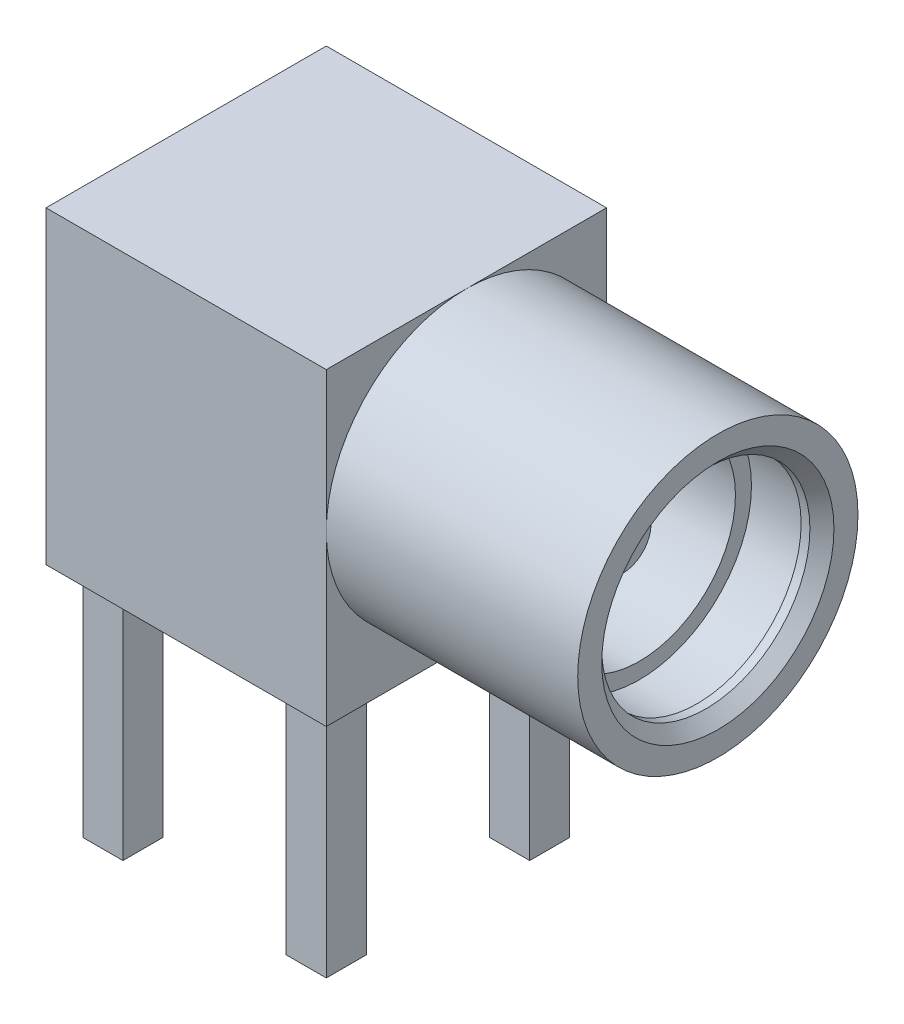
SolidWorks part; units mm, degrees
ref_plane "Front Plane" through (0, 0, 0) normal (0, 0, 1) x (1, 0, 0)
ref_plane "Top Plane" through (0, 0, 0) normal (0, 1, 0) x (1, 0, 0)
ref_plane "Right Plane" through (0, 0, 0) normal (1, 0, 0) x (0, 0, -1)
ref_plane "Plane1" through (0, 0, 20.79) normal (0, 0, -1) x (-1, 0, 0)
sketch "Sketch1" plane through (0, 0, 20.79) normal (0, 0, -1) x (-1, 0, 0)
  line L0 (-38.0125, -41.9) -> (-41.5125, -41.9)
  line L1 (-41.5125, -41.9) -> (-41.5125, -45.76)
  line L2 (-41.5125, -45.76) -> (-38.0125, -45.76)
  line L3 (-38.0125, -45.76) -> (-38.0125, -41.9)
extrude "Boss-Extrude1" add sketch "Sketch1" against normal blind 3.5
sketch "Sketch2" plane through (41.5125, 0, 0) normal (1, 0, 0) x (0, 0, -1)
  circle A0 centre (-22.54, -43.65) radius 1.75
extrude "Boss-Extrude2" add sketch "Sketch2" along normal blind 3.14
sketch "Sketch3" plane through (0, -45.76, 0) normal (0, -1, 0) x (1, 0, 0)
  line L0 (38.7425, 24.06) -> (38.7425, 23.56)
  line L1 (38.7425, 23.56) -> (38.2425, 23.56)
  line L2 (38.2425, 23.56) -> (38.2425, 24.06)
  line L3 (38.2425, 24.06) -> (38.7425, 24.06)
extrude "Boss-Extrude3" add sketch "Sketch3" along normal blind 2.95
sketch "Sketch4" plane through (0, -45.76, 0) normal (0, -1, 0) x (1, 0, 0)
  line L0 (41.2825, 21.52) -> (41.2825, 21.02)
  line L1 (41.2825, 21.02) -> (40.7825, 21.02)
  line L2 (40.7825, 21.02) -> (40.7825, 21.52)
  line L3 (40.7825, 21.52) -> (41.2825, 21.52)
extrude "Boss-Extrude4" add sketch "Sketch4" along normal blind 2.95
sketch "Sketch5" plane through (0, -45.76, 0) normal (0, -1, 0) x (1, 0, 0)
  line L0 (38.7425, 21.52) -> (38.7425, 21.02)
  line L1 (38.7425, 21.02) -> (38.2425, 21.02)
  line L2 (38.2425, 21.02) -> (38.2425, 21.52)
  line L3 (38.2425, 21.52) -> (38.7425, 21.52)
extrude "Boss-Extrude5" add sketch "Sketch5" along normal blind 2.95
sketch "Sketch6" plane through (0, -45.76, 0) normal (0, -1, 0) x (1, 0, 0)
  line L0 (41.2825, 24.06) -> (41.2825, 23.56)
  line L1 (41.2825, 23.56) -> (40.7825, 23.56)
  line L2 (40.7825, 23.56) -> (40.7825, 24.06)
  line L3 (40.7825, 24.06) -> (41.2825, 24.06)
extrude "Boss-Extrude6" add sketch "Sketch6" along normal blind 2.95
hole_wizard "#2 Clearance Hole1" positions "Sketch8" profile "Sketch7" hole size "#2" standard "ANSI Inch"
sketch "Sketch8" plane through (44.6525, 0, 0) normal (1, 0, 0) x (0, 0, -1)
  point P0 (-22.54, -43.65)
sketch "Sketch7" plane through (44.6525, -43.65, 22.54) normal (0, 1, 0) x (0, 0, -1)
  line L0 (0, 0) -> (0, 2.59)
  line L1 (0, 2.59) -> (1.2, 2.59)
  line L2 (1.2, 2.59) -> (1.2, 0)
  line L5 (1.2, 0) -> (0, 0)
  line L10 (0, 2.59) -> (-1.2, 2.59) construction
  line L11 (0, -6.35) -> (0, 107.95) construction
  dimension "Hole Dia." = 2.4
  dimension "Hole Depth" = 2.59
  dimension "Drill Angle" = 180
ref_plane "Plane2" through (0, 0, 22.54) normal (0, 0, 1) x (1, 0, 0)
sketch "Sketch9" plane through (0, 0, 22.54) normal (0, 0, 1) x (1, 0, 0)
  line L0 (40.1175, -45.76) -> (39.7625, -45.76)
  line L1 (39.7625, -45.76) -> (39.7625, -48.71)
  line L2 (39.7625, -48.71) -> (39.9675, -48.71)
  line L3 (39.9675, -48.71) -> (40.1175, -48.56)
  line L4 (40.1175, -48.56) -> (40.1175, -45.76)
  line L5 (39.7625, -45.76) -> (39.7625, -48.71) construction
revolve "Revolve1" add sketch "Sketch9" angle 360 about L5
sketch "Sketch10" plane through (0, 0, 22.54) normal (0, 0, 1) x (1, 0, 0)
  line L0 (44.6525, -42.45) -> (44.6525, -42.2)
  line L1 (44.6525, -42.2) -> (44.5025, -42.35)
  line L2 (44.5025, -42.35) -> (44.3925, -42.35)
  line L3 (44.3925, -42.35) -> (44.3925, -42.25)
  line L4 (44.3925, -42.25) -> (43.6725, -42.25)
  line L5 (43.6725, -42.25) -> (43.6725, -42.45)
  line L6 (43.6725, -42.45) -> (44.6525, -42.45)
  line L7 (43.6725, -43.65) -> (44.6525, -43.65) construction
revolve "Cut-Revolve1" cut sketch "Sketch10" angle 360 about L7
sketch "Sketch11" plane through (0, 0, 22.54) normal (0, 0, 1) x (1, 0, 0)
  line L0 (42.0625, -43.295) -> (42.0625, -43.65)
  line L1 (42.0625, -43.65) -> (43.4625, -43.65)
  line L2 (43.4625, -43.65) -> (43.4625, -43.295)
  line L3 (43.4625, -43.295) -> (42.0625, -43.295)
  line L4 (42.0625, -43.65) -> (43.4625, -43.65) construction
revolve "Revolve2" add sketch "Sketch11" angle 360 about L4
